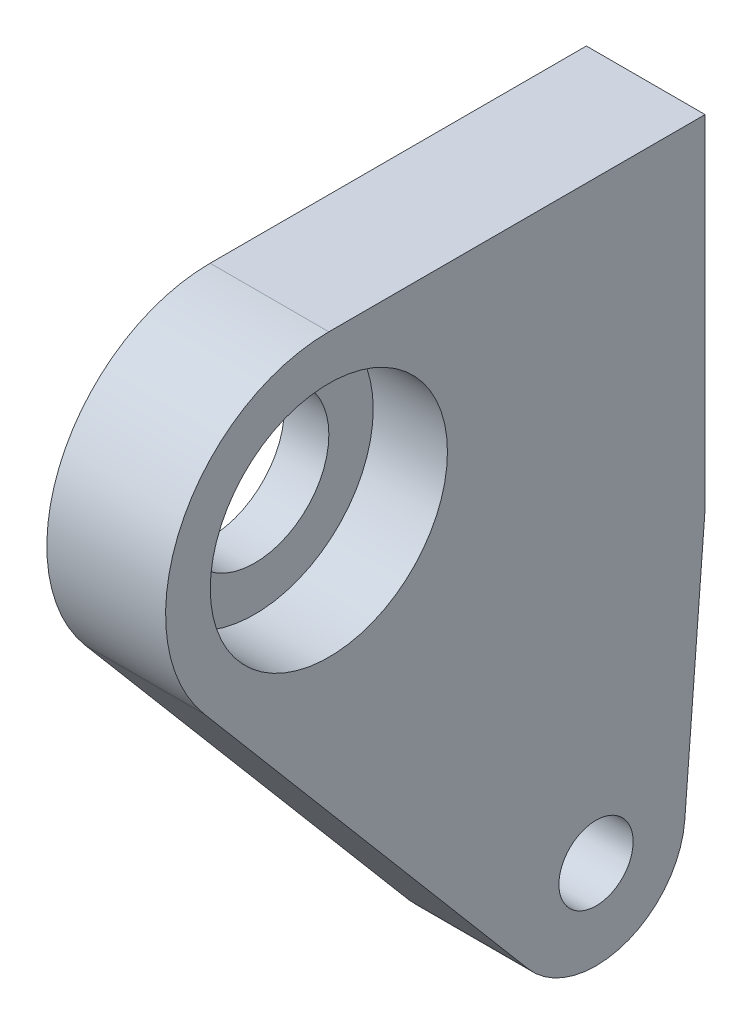
SolidWorks part; units mm, degrees
material "POM Acetal Copolymer"
ref_plane "Front Plane" through (0, 0, 0) normal (0, 0, 1) x (1, 0, 0)
ref_plane "Top Plane" through (0, 0, 0) normal (0, 1, 0) x (1, 0, 0)
ref_plane "Right Plane" through (0, 0, 0) normal (1, 0, 0) x (0, 0, -1)
sketch "Sketch27" plane through (0, 0, 0) normal (1, 0, 0) x (0, 0, -1)
  line L0 (12, 48) -> (37.3494, 48)
  line L1 (37.3494, 48) -> (37.3494, 25)
  line L3 (12, 37) -> (29.3494, 37) construction
  line L4 (29.3494, 37) -> (29.3494, 55) construction
  line L5 (37.3494, 25) -> (35.9817, 7.5317)
  line L6 (3.6046, 29.8925) -> (25.4207, 4.1232)
  line L7 (29.3494, 55) -> (12, 37) construction
  line L8 (0, 0) -> (60, 0) construction
  line L9 (0, 0) -> (0, 58) construction
  line L10 (0, 58) -> (60, 58) construction
  line L11 (60, 0) -> (60, 58) construction
  arc A0 (12, 48) -> (3.6046, 29.8925) centre (12, 37) ccw
  circle A3 centre (12, 37) radius 8 construction
  arc A4 (35.9817, 7.5317) -> (25.4207, 4.1232) centre (30, 8) cw
  circle A5 centre (12, 37) radius 5
  circle A6 centre (30, 8) radius 2.5
  dimension "D9" = 6
  dimension "D10" = 5
  dimension "D11" = 8
  dimension "D12" = 10
  dimension "D13" = 11
  dimension "D6" = 25
  dimension "D16" = 16
  dimension "D1" = 60
  dimension "D2" = 58
  dimension "D3" = 37
  dimension "D4" = 12
  dimension "D5" = 30
  dimension "D7" = 8
  dimension "D8" = 18
  dimension "D17" = 25
extrude "Boss-Extrude1" add sketch "Sketch27" along normal blind 8
hole_wizard "Tap Drill for M3 Tap1" positions "Sketch32" profile "Sketch31" hole size "M3" standard "ISO"
sketch "Sketch32" plane through (0, 0, -37.3494) normal (0, 0, -1) x (-1, 0, 0)
  line L3 (-8, 48) -> (0, 48) construction
  line L5 (0, 25) -> (0, 48) construction
  point P0 (-3, 32)
  point P2 (-3, 44)
  dimension "D1" = 3
  dimension "D2" = 12
  dimension "D3" = 4
sketch "Sketch31" plane through (3, 32, -37.3494) normal (1, 0, 0) x (0, 1, 0)
  line L0 (0, 0) -> (0, 10.7511)
  line L1 (0, 10.7511) -> (1.25, 10)
  line L2 (1.25, 10) -> (1.25, 0)
  line L5 (1.25, 0) -> (0, 0)
  line L10 (0, 10.7511) -> (-1.25, 10) construction
  line L11 (0, -6.35) -> (0, 107.95) construction
  dimension "Hole Dia." = 2.5
  dimension "Hole Depth" = 10
  dimension "Drill Angle" = 118
sketch "Sketch33" plane through (8, 0, 0) normal (1, 0, 0) x (0, 0, -1)
  circle A0 centre (12, 37) radius 7.99
  dimension "D1" = 15.98
extrude "Cut-Extrude2" cut sketch "Sketch33" against normal blind 5
